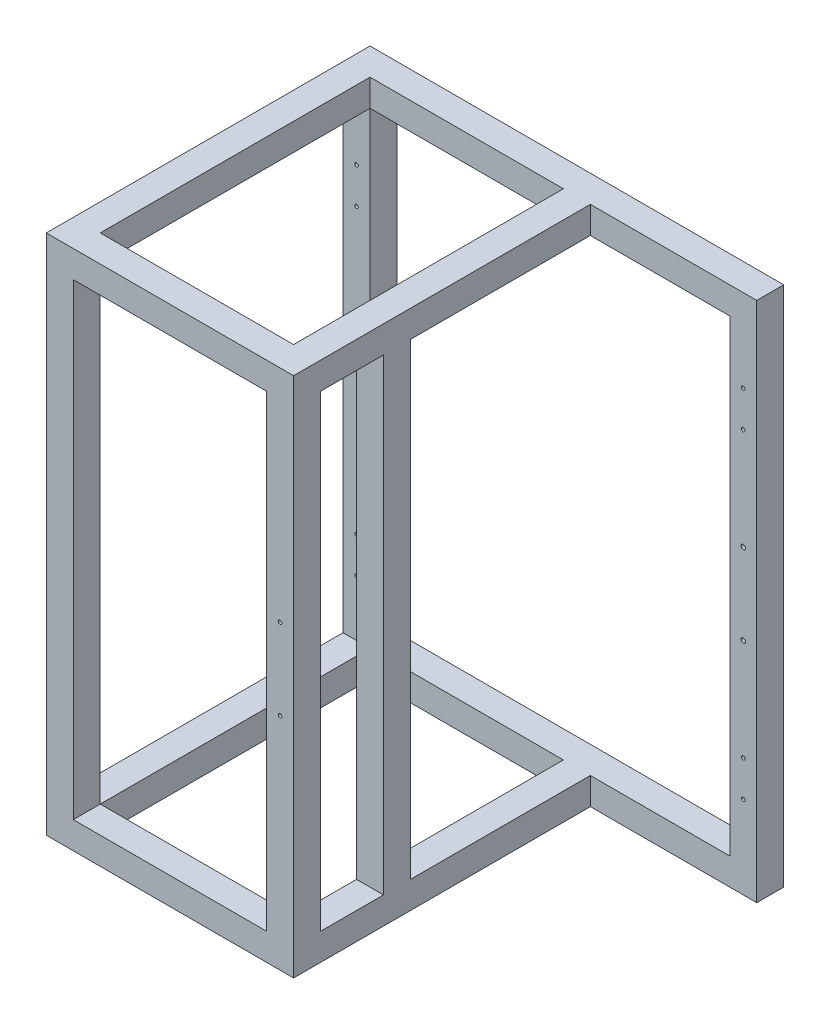
SolidWorks part; units mm, degrees
ref_plane "Płaszczyzna przednia" through (0, 0, 0) normal (0, 0, 1) x (1, 0, 0)
ref_plane "Płaszczyzna górna" through (0, 0, 0) normal (0, 1, 0) x (1, 0, 0)
ref_plane "Płaszczyzna prawa" through (0, 0, 0) normal (1, 0, 0) x (0, 0, -1)
sketch "Szkic1" plane through (0, 0, 0) normal (0, 0, 1) x (1, 0, 0)
  line L1 (-200, -260) -> (200, -260)
  line L2 (-200, -260) -> (-200, 260)
  line L3 (-200, 260) -> (200, 260)
  line L4 (200, -260) -> (200, 260)
  line L5 (-200, -260) -> (200, 260) construction
  line L6 (-200, 260) -> (200, -260) construction
  line L7 (-230, -290) -> (230, -290)
  line L8 (-230, -290) -> (-230, 290)
  line L9 (-230, 290) -> (230, 290)
  line L10 (230, -290) -> (230, 290)
  line L11 (-230, -290) -> (230, 290) construction
  line L12 (-230, 290) -> (230, -290) construction
  point P0 (0, 0)
  point P6 (0, 0)
  dimension "D1" = 520
  dimension "D2" = 580
  dimension "D3" = 400
  dimension "D4" = 460
extrude "Dodanie-wyciągnięcie1" add sketch "Szkic1" along normal blind 30
sketch "Szkic2" plane through (0, 0, 30) normal (0, 0, 1) x (1, 0, 0)
  circle A8 centre (215, 198) radius 2
  circle A9 centre (215, 158) radius 2
sketch "Szkic4" plane through (0, 0, 30) normal (0, 0, 1) x (1, 0, 0)
  circle A0 centre (215, 45) radius 2.5
  circle A1 centre (215, -45) radius 2.5
  point P0 (215, 0)
extrude "Wytnij-wyciągnięcie2" cut sketch "Szkic4" against normal blind 5
sketch "Szkic5" plane through (0, 0, 30) normal (0, 0, 1) x (1, 0, 0)
  line L0 (-200, -260) -> (200, -260) construction
  line L1 (15, -260) -> (45, -260)
  line L2 (15, -260) -> (15, -290)
  line L3 (15, -290) -> (45, -290)
  line L4 (45, -260) -> (45, -290)
  line L5 (-230, -290) -> (230, -290) construction
  line L6 (200, 260) -> (-200, 260) construction
  line L7 (15, 260) -> (45, 260)
  line L8 (15, 260) -> (15, 290)
  line L9 (15, 290) -> (45, 290)
  line L10 (45, 260) -> (45, 290)
  line L11 (230, 290) -> (-230, 290) construction
  dimension "D1" = 30
  dimension "D2" = 30
extrude "Dodanie-wyciągnięcie3" add sketch "Szkic5" along normal blind 330
sketch "Szkic6" plane through (0, 260, 0) normal (0, -1, 0) x (1, 0, 0)
  line L0 (15, 360) -> (15, 30) construction
  line L1 (15, 230) -> (45, 230)
  line L2 (15, 230) -> (15, 260)
  line L3 (15, 260) -> (45, 260)
  line L4 (45, 230) -> (45, 260)
  line L5 (45, 360) -> (45, 30) construction
  point P8 (0, 0)
  dimension "D1" = 30
extrude "Dodanie-wyciągnięcie4" add sketch "Szkic6" along normal up to next
sketch "Szkic7" plane through (0, 260, 0) normal (0, -1, 0) x (-1, 0, 0)
  line L0 (-45, -360) -> (-45, -260) construction
  line L1 (-15, -360) -> (-45, -360)
  line L2 (-15, -360) -> (-15, -330)
  line L3 (-15, -330) -> (-45, -330)
  line L4 (-45, -360) -> (-45, -330)
  dimension "D1" = 30
extrude "Dodanie-wyciągnięcie5" add sketch "Szkic7" along normal up to next
sketch "Szkic8" plane through (0, 0, 30) normal (0, 0, 1) x (1, 0, 0)
  line L1 (-230, 290) -> (-200, 290)
  line L2 (-230, 290) -> (-230, 260)
  line L3 (-230, 260) -> (-200, 260)
  line L4 (-200, 290) -> (-200, 260)
  line L5 (-230, -290) -> (-200, -290)
  line L6 (-230, -290) -> (-230, -260)
  line L7 (-230, -260) -> (-200, -260)
  line L8 (-200, -290) -> (-200, -260)
extrude "Dodanie-wyciągnięcie6" add sketch "Szkic8" along normal blind 330
sketch "Szkic9" plane through (-200, 0, 0) normal (1, 0, 0) x (0, 0, -1)
  line L0 (-360, 290) -> (-30, 290) construction
  line L1 (-360, 260) -> (-330, 260)
  line L2 (-360, 260) -> (-360, 290)
  line L3 (-360, 290) -> (-330, 290)
  line L4 (-330, 260) -> (-330, 290)
  line L5 (-360, -260) -> (-30, -260) construction
  line L6 (-360, -290) -> (-330, -290)
  line L7 (-360, -290) -> (-360, -260)
  line L8 (-360, -260) -> (-330, -260)
  line L9 (-330, -290) -> (-330, -260)
  dimension "D1" = 30
extrude "Dodanie-wyciągnięcie7" add sketch "Szkic9" along normal up to next
sketch "Szkic10" plane through (0, 260, 0) normal (0, -1, 0) x (1, 0, 0)
  line L0 (-230, 360) -> (15, 360) construction
  line L1 (-230, 360) -> (-200, 360)
  line L2 (-230, 360) -> (-230, 330)
  line L3 (-230, 330) -> (-200, 330)
  line L4 (-200, 360) -> (-200, 330)
  line L5 (15, 330) -> (-200, 330) construction
  dimension "D1" = 30
extrude "Dodanie-wyciągnięcie8" add sketch "Szkic10" along normal up to next
sketch "Szkic11" plane through (15, 0, 0) normal (-1, 0, 0) x (0, 0, 1)
  circle A0 centre (245, 25) radius 2
  circle A1 centre (245, -25) radius 2
  point P0 (245, -25)
  point P1 (245, 25)
  point P2 (245, -25)
  point P7 (0, 0)
  point P8 (0, 0)
extrude "Wytnij-wyciągnięcie3" cut sketch "Szkic11" against normal blind 5
sketch "Szkic12" plane through (0, 0, 360) normal (0, 0, 1) x (1, 0, 0)
  circle A0 centre (30, -45) radius 2
  circle A1 centre (30, 45) radius 2
extrude "Wytnij-wyciągnięcie4" cut sketch "Szkic12" against normal blind 5
extrude "Wytnij-wyciągnięcie5" cut sketch "Szkic2" against normal blind 5
mirror "Lustro1" about plane through (0, 0, 0) normal (1, 0, 0) of "Wytnij-wyciągnięcie5"
mirror "Lustro2" about plane through (0, 0, 0) normal (0, 1, 0) of "Lustro1", "Wytnij-wyciągnięcie5"
